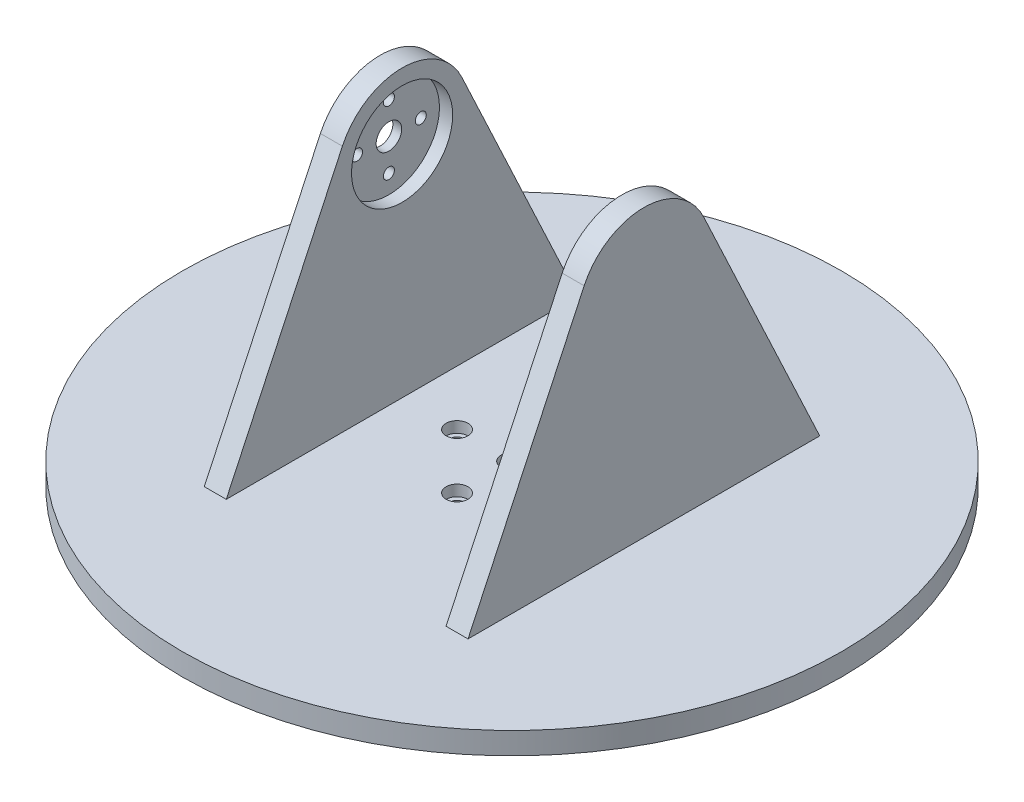
SolidWorks part; units mm, degrees
ref_plane "Front Plane" through (0, 0, 0) normal (0, 0, 1) x (1, 0, 0)
ref_plane "Top Plane" through (0, 0, 0) normal (0, 1, 0) x (1, 0, 0)
ref_plane "Right Plane" through (0, 0, 0) normal (1, 0, 0) x (0, 0, -1)
sketch "Sketch1" plane through (0, 0, 0) normal (0, 1, 0) x (1, 0, 0)
  circle A0 centre (0, 0) radius 75
  dimension "D1" = 150
extrude "Boss-Extrude1" add sketch "Sketch1" along normal blind 5 contours A0
sketch "Sketch2" plane through (0, 5, 0) normal (0, 1, 0) x (1, 0, 0)
  line L1 (-30, -40) -> (-25, -40)
  line L2 (-30, -40) -> (-30, 40)
  line L3 (-30, 40) -> (-25, 40)
  line L4 (-25, -40) -> (-25, 40)
  line L5 (-30, -40) -> (-25, 40) construction
  line L6 (-30, 40) -> (-25, -40) construction
  point P0 (-30, 0)
  dimension "D1" = 80
  dimension "D2" = 5
  dimension "D3" = 30
sketch "Sketch3" plane through (0, 5, 0) normal (0, 1, 0) x (1, 0, 0)
  line L1 (25, -40) -> (30, -40)
  line L2 (25, -40) -> (25, 40)
  line L3 (25, 40) -> (30, 40)
  line L4 (30, -40) -> (30, 40)
  line L5 (25, -40) -> (30, 40) construction
  line L6 (25, 40) -> (30, -40) construction
  dimension "D1" = 80
  dimension "D2" = 5
  dimension "D3" = 30
sketch3d "3DSketch1"
  line L0 (-25, 5, 40) -> (-25, 5, -40) construction
  line L2 (-30, 5, 40) -> (-25, 5, 40) construction
sketch "Sketch4" plane through (-25, 0, 0) normal (-1, 0, 0) x (0, 0, 1)
  line L0 (40, 5) -> (-40, 5) construction
  line L1 (-13.5822, 61.3658) -> (-40, 5)
  line L2 (13.5822, 61.3658) -> (40, 5)
  line L3 (-40, 5) -> (40, 5) construction
  line L4 (-40, 5) -> (40, 5)
  arc A0 (13.5822, 61.3658) -> (-13.5822, 61.3658) centre (0, 55) ccw
  dimension "D1" = 15
  dimension "D2" = 50
extrude "Boss-Extrude2" add sketch "Sketch4" along normal blind 5
sketch3d "3DSketch2"
  line L0 (25, 5, 40) -> (25, 5, -40) construction
  line L1 (25, 5, -40) -> (30, 5, -40) construction
sketch "Sketch5" plane through (25, 0, 0) normal (-1, 0, 0) x (0, 0, 1)
  line L0 (40, 5) -> (-40, 5) construction
  line L1 (13.5822, 61.3658) -> (40, 5)
  line L2 (40, 5) -> (-40, 5)
  line L3 (-13.5822, 61.3658) -> (-40, 5)
  arc A0 (13.5822, 61.3658) -> (-13.5822, 61.3658) centre (0, 55) ccw
  dimension "D1" = 15
  dimension "D2" = 50
extrude "Boss-Extrude3" add sketch "Sketch5" against normal blind 5
sketch "Sketch6" plane through (-30, 0, 0) normal (-1, 0, 0) x (0, 0, 1)
  circle A0 centre (0, 55) radius 1.5
  dimension "D1" = 3
extrude "Cut-Extrude1" cut sketch "Sketch6" against normal blind 5
sketch "Sketch7" plane through (-30, 0, 0) normal (-1, 0, 0) x (0, 0, 1)
  circle A0 centre (0, 55) radius 2.9
  dimension "D1" = 5.8
extrude "Cut-Extrude2" cut sketch "Sketch7" against normal blind 2.5
sketch "Sketch8" plane through (-30, 0, 0) normal (-1, 0, 0) x (0, 0, 1)
  circle A0 centre (0, 62.25) radius 0.6
  circle A1 centre (0, 55) radius 1.5 construction
  dimension "D1" = 1.2
  dimension "D2" = 7.25
extrude "Cut-Extrude3" cut sketch "Sketch8" against normal blind 5 contours A0
pattern_circular "CirPattern1" count 4 over 360 about axis through (0, 55, 0) along (1, 0, 0) of "Cut-Extrude3"
sketch "Sketch10" plane through (-30, 0, 0) normal (-1, 0, 0) x (0, 0, 1)
  circle A0 centre (0, 62.25) radius 1.25
  dimension "D1" = 2.5
extrude "Cut-Extrude4" cut sketch "Sketch10" against normal blind 3
pattern_circular "CirPattern2" count 4 over 360 about axis through (0, 55, 0) along (1, 0, 0) of "Cut-Extrude4"
sketch "Sketch11" plane through (0, 5, 0) normal (0, 1, 0) x (1, 0, 0)
  circle A0 centre (0, 0) radius 1.5
  dimension "D1" = 3
extrude "Cut-Extrude5" cut sketch "Sketch11" against normal blind 5
sketch "Sketch12" plane through (0, 5, 0) normal (0, 1, 0) x (1, 0, 0)
  circle A0 centre (0, 12.5) radius 1.5
  dimension "D1" = 3
  dimension "D2" = 12.5
extrude "Cut-Extrude6" cut sketch "Sketch12" against normal blind 5
pattern_circular "CirPattern3" count 4 over 360 about axis through (0, 0, 0) along (0, 1, 0) of "Cut-Extrude6"
sketch "Sketch13" plane through (0, 5, 0) normal (0, 1, 0) x (1, 0, 0)
  circle A0 centre (0, 12.5) radius 2.4883
extrude "Cut-Extrude7" cut sketch "Sketch13" against normal blind 2.5
pattern_circular "CirPattern4" count 4 over 360 about axis through (0, 0, 0) along (0, 1, 0) of "Cut-Extrude7"
sketch "Sketch14" plane through (0, 5, 0) normal (0, 1, 0) x (1, 0, 0)
  circle A0 centre (0, 0) radius 2.4611
extrude "Cut-Extrude8" cut sketch "Sketch14" against normal blind 2.5
sketch "Sketch16" plane through (-25, 0, 0) normal (1, 0, 0) x (0, 0, -1)
  circle A0 centre (0, 55) radius 11.5
  dimension "D1" = 23
extrude "Cut-Extrude10" cut sketch "Sketch16" against normal blind 3 contours A0
sketch "Sketch17" plane through (0, 0, 0) normal (0, -1, 0) x (-1, 0, 0)
  circle A0 centre (0, 0) radius 16
  dimension "D1" = 32
